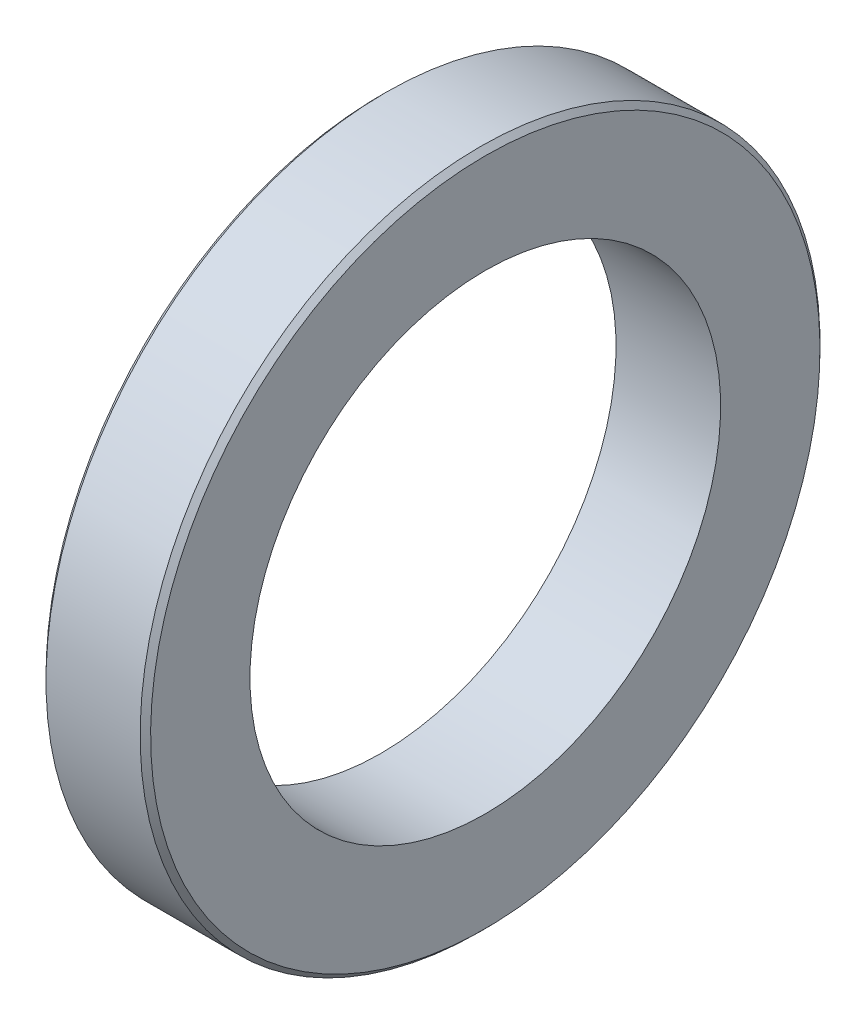
SolidWorks part; units mm, degrees
ref_plane "Front Plane" through (0, 0, 0) normal (0, 0, 1) x (1, 0, 0)
ref_plane "Top Plane" through (0, 0, 0) normal (0, 1, 0) x (1, 0, 0)
ref_plane "Right Plane" through (0, 0, 0) normal (1, 0, 0) x (0, 0, -1)
sketch "Sketch1" plane through (0, 0, 0) normal (0, 0, 1) x (1, 0, 0)
  line L0 (-32.2482, 0) -> (32.2482, 0) construction
  line L2 (-5, -22.5) -> (5, -22.5)
  line L3 (-5, -22.5) -> (-5, -32.5)
  line L4 (-5, -32.5) -> (5, -32.5)
  line L5 (5, -22.5) -> (5, -32.5)
  line L6 (-5, -22.5) -> (5, -32.5) construction
  line L7 (-5, -32.5) -> (5, -22.5) construction
  point P1 (0, -27.5)
  point P4 (0, 0)
  dimension "D1" = 45
  dimension "D2" = 65
  dimension "D3" = 10
revolve "Revolve1" add sketch "Sketch1" angle 360 about L0
chamfer "Chamfer1" distance 0.5 angle 45 2 edges at (-5, -32.5, 0) (5, -32.5, 0)
